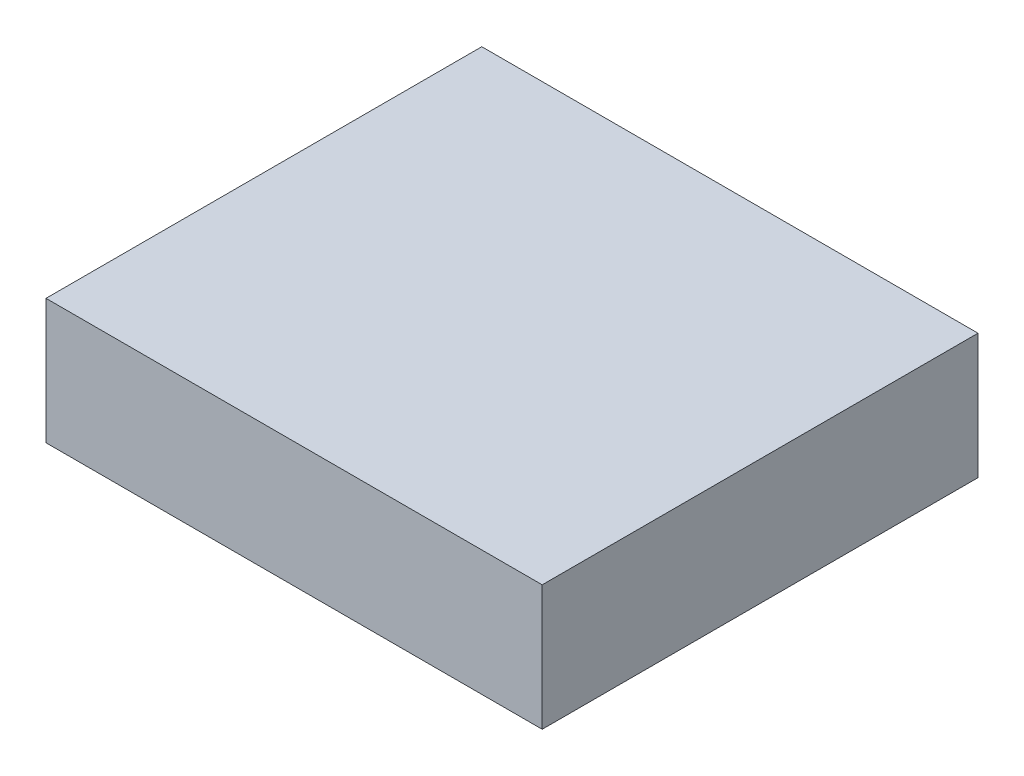
SolidWorks part; units mm, degrees
ref_plane "Front Plane" through (0, 0, 0) normal (0, 0, 1) x (1, 0, 0)
ref_plane "Top Plane" through (0, 0, 0) normal (0, 1, 0) x (1, 0, 0)
ref_plane "Right Plane" through (0, 0, 0) normal (1, 0, 0) x (0, 0, -1)
sketch "Sketch1" plane through (0, 0, 0) normal (0, 1, 0) x (1, 0, 0)
  line L1 (-57.5, 50.5) -> (57.5, 50.5)
  line L2 (-57.5, 50.5) -> (-57.5, -50.5)
  line L3 (-57.5, -50.5) -> (57.5, -50.5)
  line L4 (57.5, 50.5) -> (57.5, -50.5)
  line L5 (-57.5, 50.5) -> (57.5, -50.5) construction
  line L6 (-57.5, -50.5) -> (57.5, 50.5) construction
  point P0 (0, 0)
  dimension "D1" = 115
  dimension "D2" = 101
extrude "Boss-Extrude1" add sketch "Sketch1" along normal blind 29
